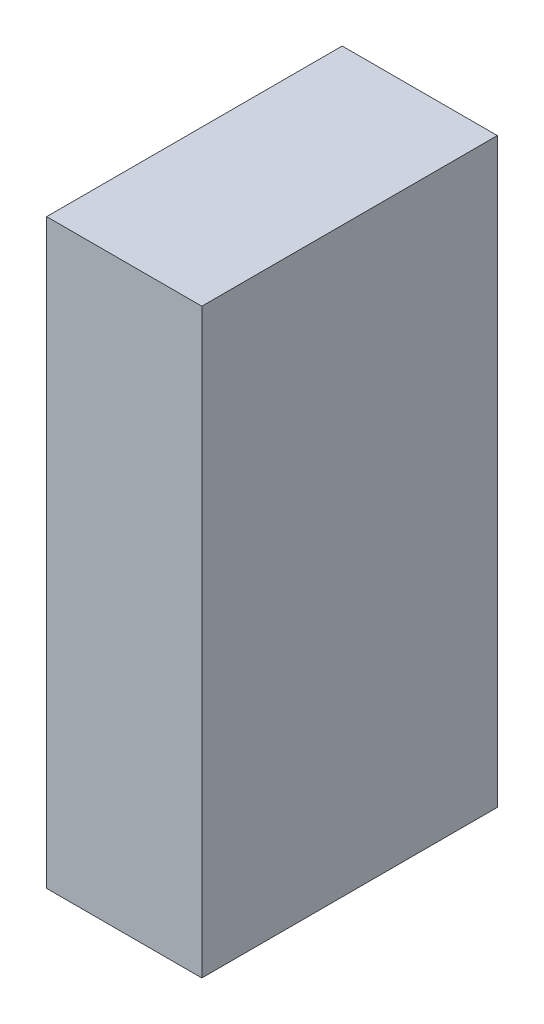
SolidWorks part; units mm, degrees
ref_plane "Alzado" through (0, 0, 0) normal (0, 0, 1) x (1, 0, 0)
ref_plane "Planta" through (0, 0, 0) normal (0, 1, 0) x (1, 0, 0)
ref_plane "Vista lateral" through (0, 0, 0) normal (1, 0, 0) x (0, 0, -1)
sketch "Croquis2" plane through (0, 0, 0) normal (0, 1, 0) x (1, 0, 0)
  line L1 (0, 0) -> (40, 0)
  line L2 (0, 0) -> (0, -76.2)
  line L3 (0, -76.2) -> (40, -76.2)
  line L4 (40, 0) -> (40, -76.2)
  dimension "D1" = 76.2
  dimension "D2" = 40
extrude "Saliente-Extruir1" add sketch "Croquis2" along normal blind 150
